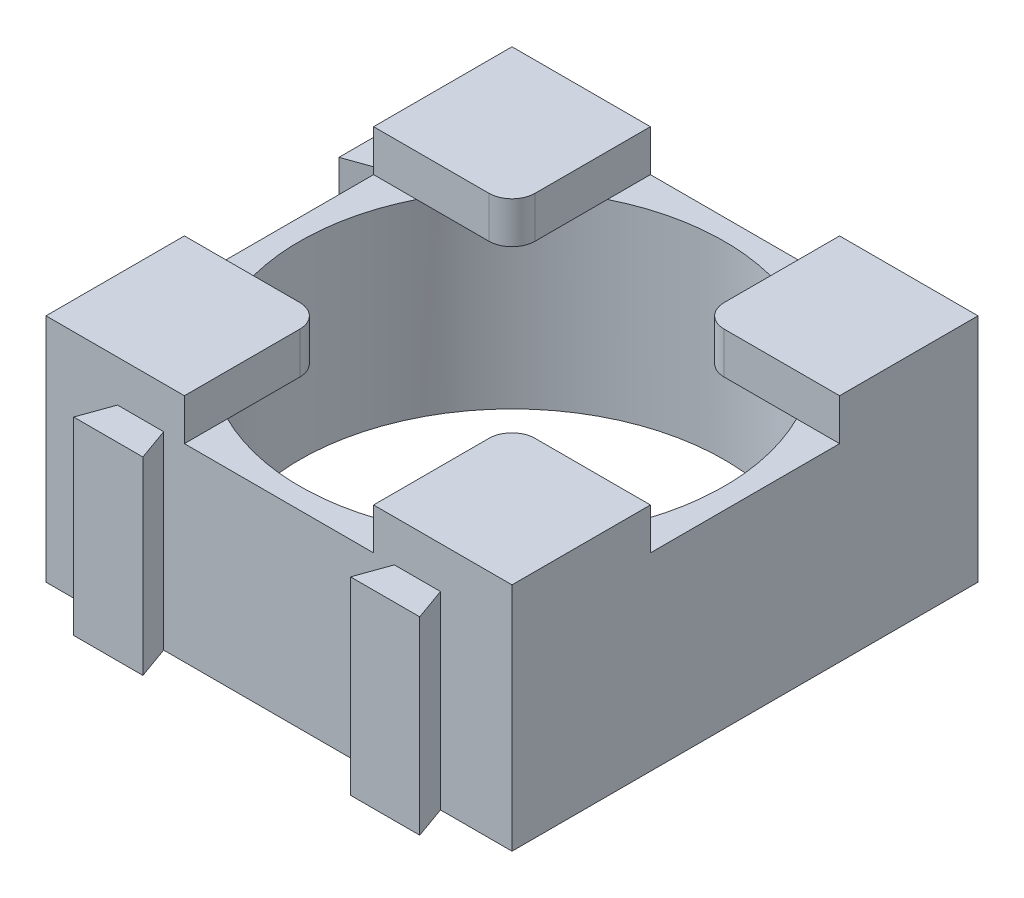
SolidWorks part; units mm, degrees
ref_plane "Front Plane" through (0, 0, 0) normal (0, 0, 1) x (1, 0, 0)
ref_plane "Top Plane" through (0, 0, 0) normal (0, 1, 0) x (1, 0, 0)
ref_plane "Right Plane" through (0, 0, 0) normal (1, 0, 0) x (0, 0, -1)
sketch "Sketch1" plane through (0, 0, 0) normal (0, 1, 0) x (1, 0, 0)
  line L0 (-14.0032, 0) -> (15.5031, 0) construction
  line L1 (-10.1, 10.1) -> (-7, 10.1)
  line L2 (-10.1, 10.1) -> (-10.1, 6.5)
  line L3 (-10.1, -10.1) -> (-7, -10.1)
  line L4 (10.1, 10.1) -> (10.1, 6.5)
  line L5 (0, 12.8597) -> (0, -11.7289) construction
  line L6 (-10.1, 6.5) -> (-11.5, 7)
  line L7 (-11.5, 7) -> (-11.5, 4)
  line L8 (-11.5, 4) -> (-10.1, 4.5)
  line L12 (-10.1, 4.5) -> (-10.1, -4.5)
  line L13 (10.1, 4.5) -> (10.1, -4.5)
  line L14 (7, 10.1) -> (7.5, 8.7)
  line L15 (7.5, 8.7) -> (4.5, 8.7)
  line L16 (4.5, 8.7) -> (5, 10.1)
  line L17 (7, 10.1) -> (10.1, 10.1)
  line L18 (-7, -10.1) -> (-7.5, -11.5)
  line L19 (-7.5, -11.5) -> (-4.5, -11.5)
  line L20 (-4.5, -11.5) -> (-5, -10.1)
  line L21 (-5, -10.1) -> (5, -10.1)
  line L22 (-11.5, -4) -> (-10.1, -4.5)
  line L23 (-11.5, -7) -> (-11.5, -4)
  line L24 (-10.1, -6.5) -> (-11.5, -7)
  line L25 (-10.1, -6.5) -> (-10.1, -10.1)
  line L26 (4.5, -11.5) -> (5, -10.1)
  line L27 (7.5, -11.5) -> (4.5, -11.5)
  line L28 (7, -10.1) -> (7.5, -11.5)
  line L29 (7, -10.1) -> (10.1, -10.1)
  line L30 (-4.5, 8.7) -> (-5, 10.1)
  line L31 (-7.5, 8.7) -> (-4.5, 8.7)
  line L32 (-7, 10.1) -> (-7.5, 8.7)
  line L33 (-5, 10.1) -> (5, 10.1)
  line L34 (10.1, -6.5) -> (10.1, -4.5)
  line L35 (10.1, 4.5) -> (10.1, 6.5)
  line L37 (10.1, -6.5) -> (10.1, -10.1)
  circle A4 centre (0, 0) radius 9.2
  point P7 (-10.1, -10.1)
  point P10 (10.1, -10.1)
  point P13 (10.1, 10.1)
  dimension "D5" = 4.5
  dimension "D6" = 18.4
  dimension "D1" = 20.2
  dimension "D2" = 20.2
  dimension "D3" = 10.1
  dimension "D4" = 10.1
  dimension "D7" = 1.4
  dimension "D10" = 3
  dimension "D11" = 2
  dimension "D14" = 2
  dimension "D15" = 3
  dimension "D16" = 0.5
  dimension "D17" = 4.5
  dimension "D18" = 1.4
  dimension "D19" = 3
  dimension "D20" = 2
  dimension "D21" = 0.5
  dimension "D22" = 1.4
  dimension "D23" = 4.5
extrude "Boss-Extrude1" add sketch "Sketch1" along normal blind 8.2
sketch "Sketch2" plane through (0, 8.2, 0) normal (0, 1, 0) x (1, 0, 0)
  line L0 (-4.1, 10.1) -> (-4.1, 5.1)
  line L1 (-10.1, 4.5) -> (-10.1, -4.5) construction
  line L2 (-5.1, 4.1) -> (-10.1, 4.1)
  line L3 (10.1, 4.1) -> (10.1, 10.1)
  line L4 (-10.1, 10.1) -> (-4.1, 10.1)
  line L5 (-10.1, 4.1) -> (-10.1, 10.1)
  line L6 (0, 10.1) -> (0, -10.1) construction
  line L7 (-10.1, 0) -> (10.1, 0) construction
  line L8 (10.1, 10.1) -> (4.1, 10.1)
  line L9 (5.1, 4.1) -> (10.1, 4.1)
  line L10 (4.1, 10.1) -> (4.1, 5.1)
  line L11 (4.1, -10.1) -> (4.1, -5.1)
  line L12 (5.1, -4.1) -> (10.1, -4.1)
  line L13 (10.1, -10.1) -> (4.1, -10.1)
  line L14 (-10.1, -4.1) -> (-10.1, -10.1)
  line L15 (-10.1, -10.1) -> (-4.1, -10.1)
  line L16 (10.1, -4.1) -> (10.1, -10.1)
  line L17 (-5.1, -4.1) -> (-10.1, -4.1)
  line L18 (-4.1, -10.1) -> (-4.1, -5.1)
  line L19 (10.1, -10.1) -> (10.1, 10.1) construction
  line L20 (5, 10.1) -> (-5, 10.1) construction
  line L21 (-5, -10.1) -> (5, -10.1) construction
  arc A0 (-4.1, 5.1) -> (-5.1, 4.1) centre (-5.1, 5.1) cw
  arc A1 (4.1, 5.1) -> (5.1, 4.1) centre (5.1, 5.1) ccw
  arc A2 (4.1, -5.1) -> (5.1, -4.1) centre (5.1, -5.1) cw
  arc A3 (-4.1, -5.1) -> (-5.1, -4.1) centre (-5.1, -5.1) ccw
  dimension "D2" = 1
  dimension "D1" = 6
extrude "Boss-Extrude2" add sketch "Sketch2" along normal blind 1.8
sketch "Sketch4" plane through (0, 0, 0) normal (0, 1, 0) x (1, 0, 0)
  line L0 (0, 10.1) -> (41.5763, 10.1) construction
  line L1 (5, 10.1) -> (-5, 10.1) construction
  line L2 (-10.1, 0) -> (-10.1, -33.7152) construction
  line L3 (-10.1, 4.1) -> (-10.1, -4.1) construction
pattern_linear "LPattern1" [suppressed] count 2 spacing 20.2 along (1, 0, 0)
